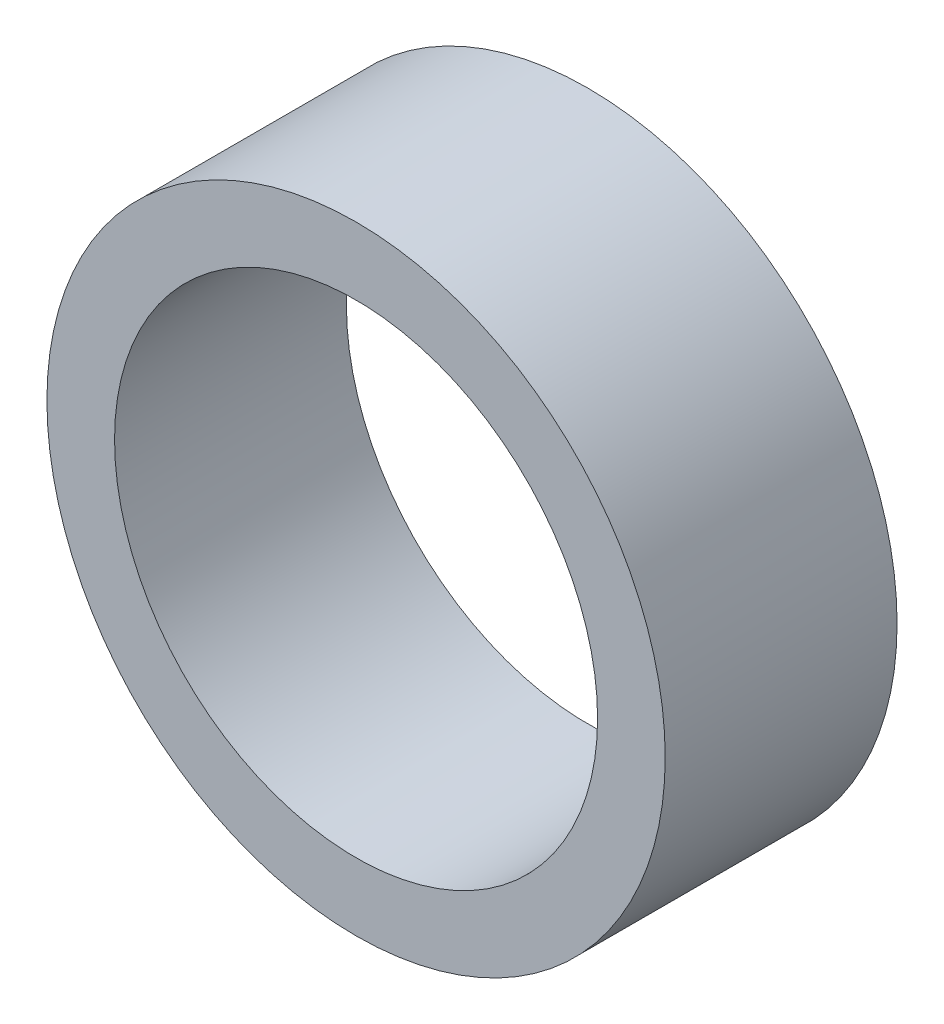
SolidWorks part; units mm, degrees
ref_plane "Front Plane" through (0, 0, 0) normal (0, 0, 1) x (1, 0, 0)
ref_plane "Top Plane" through (0, 0, 0) normal (0, 1, 0) x (1, 0, 0)
ref_plane "Right Plane" through (0, 0, 0) normal (1, 0, 0) x (0, 0, -1)
sketch "Sketch1" plane through (0, 0, 0) normal (0, 0, 1) x (1, 0, 0)
  circle A0 centre (0, 0) radius 12.5
  circle A1 centre (0, 0) radius 16
  dimension "D1" = 25
  dimension "D2" = 32
extrude "Boss-Extrude1" add sketch "Sketch1" along normal blind 12
